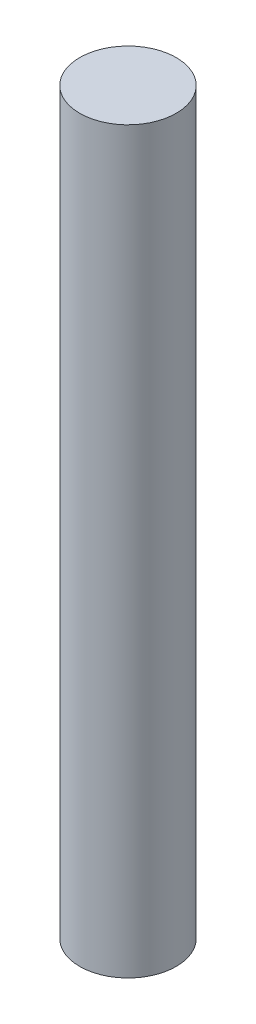
SolidWorks part; units mm, degrees
ref_plane "Front Plane" through (0, 0, 0) normal (0, 0, 1) x (1, 0, 0)
ref_plane "Top Plane" through (0, 0, 0) normal (0, 1, 0) x (1, 0, 0)
ref_plane "Right Plane" through (0, 0, 0) normal (1, 0, 0) x (0, 0, -1)
sketch "Sketch2" plane through (0, 0, 0) normal (0, 1, 0) x (1, 0, 0)
  circle A0 centre (0, 0) radius 199.136
  dimension "D1" = 398.272
extrude "Boss-Extrude1" add sketch "Sketch2" along normal blind 3048
